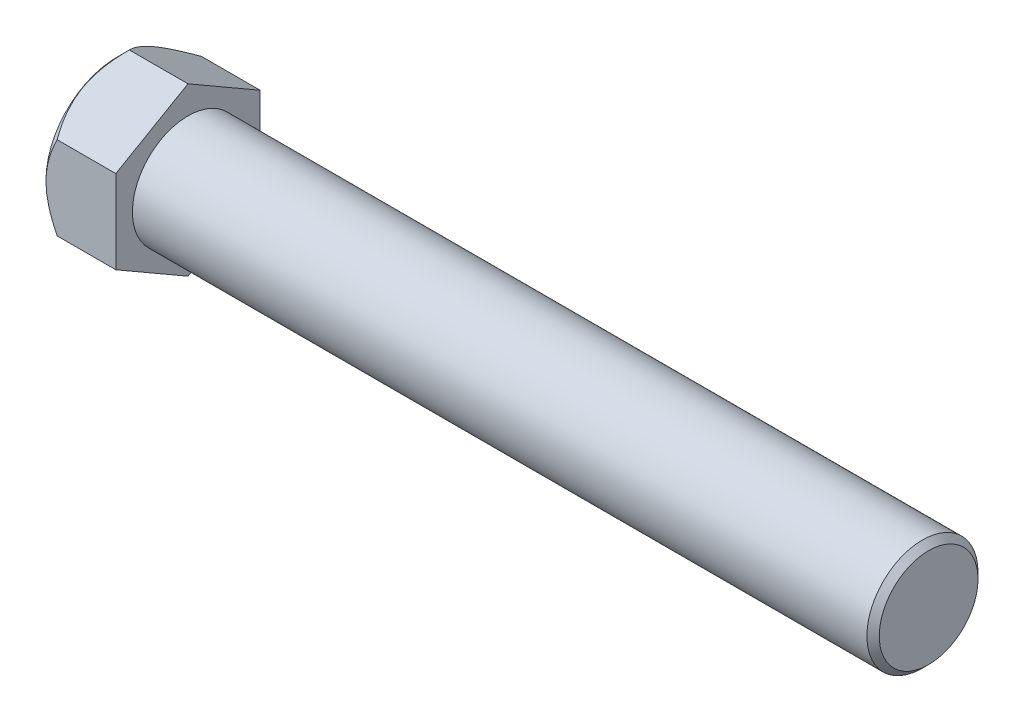
SolidWorks part; units mm, degrees
material "Plain Carbon Steel"
ref_plane "Front Plane" through (0, 0, 0) normal (0, 0, 1) x (1, 0, 0)
ref_plane "Top Plane" through (0, 0, 0) normal (0, 1, 0) x (1, 0, 0)
ref_plane "Right Plane" through (0, 0, 0) normal (1, 0, 0) x (0, 0, -1)
sketch "Sketch1" plane through (0, 0, 0) normal (1, 0, 0) x (0, 0, -1)
  line L1 (0, 13.5) -> (-11.6913, 6.75)
  line L2 (-11.6913, 6.75) -> (-11.6913, -6.75)
  line L3 (-11.6913, -6.75) -> (0, -13.5)
  line L4 (0, -13.5) -> (11.6913, -6.75)
  line L5 (11.6913, -6.75) -> (11.6913, 6.75)
  line L6 (11.6913, 6.75) -> (0, 13.5)
  circle A0 centre (0, 0) radius 11.6913 construction
  dimension "E" = 27
extrude "Extrude1" add sketch "Sketch1" along normal blind 11.5
sketch "Sketch2" plane through (0, 0, 0) normal (0, 0, 1) x (1, 0, 0)
  line L0 (2, 13.5) -> (0, 11.5)
  line L1 (11.5, 13.5) -> (0, 13.5) construction
  line L2 (0, 13.5) -> (0, 6.75) construction
  line L3 (0, 11.5) -> (0, 13.5)
  line L4 (0, 13.5) -> (2, 13.5)
  line L5 (0, 0) -> (4.7427, 0) construction
  dimension "D1" = 45
  dimension "TOPCHM" = 2
revolve "Cut-Revolve1" cut sketch "Sketch2" angle 360 about L5
sketch "Sketch3" plane through (11.5, 0, 0) normal (1, 0, 0) x (0, 0, -1)
  circle A0 centre (0, 0) radius 9
  dimension "M" = 18
extrude "Extrude2" add sketch "Sketch3" along normal blind 120
cosmetic thread "Cosmetic Thread1" parameters "B"=60, "D2"=16.4
chamfer "Chamfer1" distance 1 angle 45 1 edges at (131.5, 0, -9)
sketch "Sketch4" plane through (0, 0, 0) normal (-1, 0, 0) x (0, 0, 1)
  line L0 (-11.0559, -3.1648) -> (11.0559, -3.1648) construction
  circle A0 centre (0, 0) radius 11.5 construction
  circle A1 centre (0, 0) radius 11.5 construction
  text T0 "8.8"
extrude "Cut-Extrude1" cut sketch "Sketch4" against normal blind 0.01
